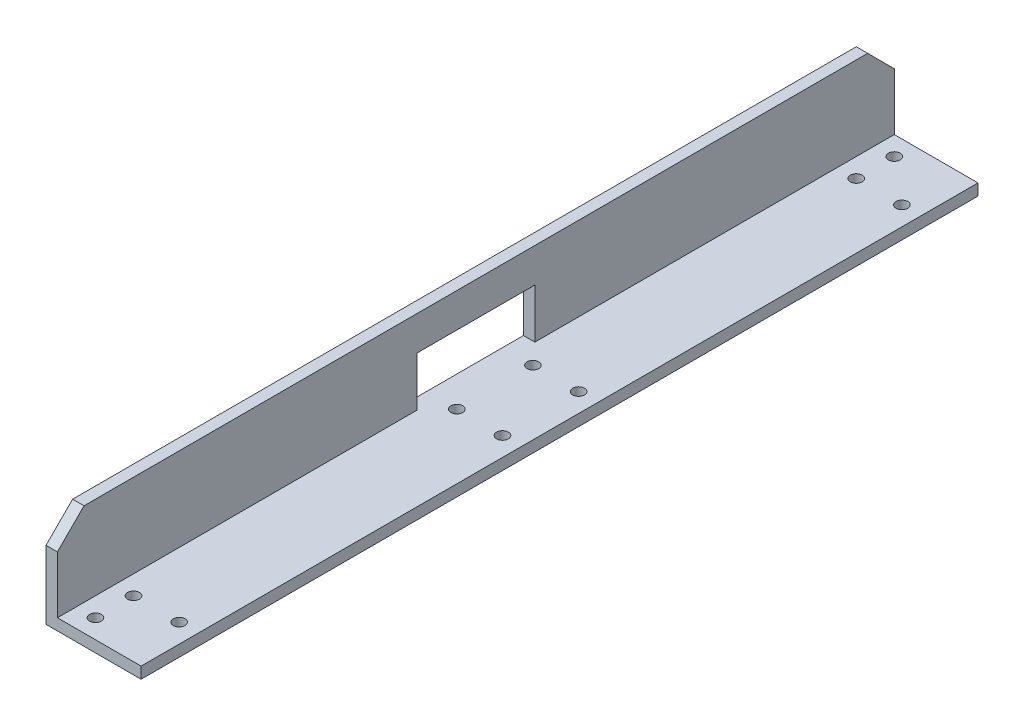
SolidWorks part; units mm, degrees
ref_plane "Front Plane" through (0, 0, 0) normal (0, 0, 1) x (1, 0, 0)
ref_plane "Top Plane" through (0, 0, 0) normal (0, 1, 0) x (1, 0, 0)
ref_plane "Right Plane" through (0, 0, 0) normal (1, 0, 0) x (0, 0, -1)
sketch "Sketch1" plane through (0, 0, 0) normal (0, 0, 1) x (1, 0, 0)
  line L0 (0, 0) -> (0, 25)
  line L1 (0, 25) -> (3, 25)
  line L2 (3, 25) -> (3, 3)
  line L3 (3, 3) -> (25, 3)
  line L4 (25, 3) -> (25, 0)
  line L5 (25, 0) -> (0, 0)
  dimension "D1" = 3
  dimension "D2" = 25
extrude "Boss-Extrude1" add sketch "Sketch1" along normal blind 220
sketch "Sketch2" plane through (3, 0, 0) normal (1, 0, 0) x (0, 0, -1)
  line L0 (-220, 3) -> (0, 3) construction
  line L1 (-125.5, 3) -> (-94.5, 3)
  line L2 (-125.5, 3) -> (-125.5, 16)
  line L3 (-125.5, 16) -> (-94.5, 16)
  line L4 (-94.5, 3) -> (-94.5, 16)
  line L5 (-110, 16) -> (-110, 0) construction
  line L6 (-220, 0) -> (0, 0) construction
  dimension "D1" = 31
  dimension "D2" = 13
extrude "Cut-Extrude1" cut sketch "Sketch2" against normal blind 10
sketch "Sketch3" plane through (0, 0, 0) normal (0, -1, 0) x (1, 0, 0)
  line L0 (8, 220) -> (8, 0) construction
  line L2 (0, 0) -> (25, 0) construction
  line L3 (0, 220) -> (0, 0) construction
  line L4 (-195, 220) -> (25, 220) construction
  line L8 (8, 120) -> (20, 120) construction
  line L9 (25, 220) -> (25, 0) construction
  line L10 (20, 100) -> (20, 120) construction
  line L11 (20, 100) -> (8, 100) construction
  line L12 (0, 220) -> (25, 220) construction
  line L13 (20, 205) -> (8, 205) construction
  line L14 (8, 15) -> (20, 15) construction
  line L15 (20, 15) -> (20, 205) construction
  line L16 (0, 110) -> (25, 110) construction
  circle A0 centre (8, 100) radius 1.55
  circle A1 centre (8, 120) radius 1.55
  circle A2 centre (8, 215) radius 1.55
  circle A3 centre (8, 205) radius 1.55
  circle A4 centre (8, 15) radius 1.55
  circle A5 centre (8, 5) radius 1.55
  circle A6 centre (20, 120) radius 1.55
  circle A7 centre (20, 100) radius 1.55
  circle A8 centre (20, 15) radius 1.55
  circle A9 centre (20, 205) radius 1.55
  dimension "D2" = 3.1
  dimension "D1" = 8
  dimension "D3" = 5
  dimension "D4" = 10
  dimension "D5" = 10
  dimension "D6" = 20
  dimension "D7" = 10
  dimension "D8" = 5
  dimension "D9" = 5
  dimension "D10" = 5
extrude "Cut-Extrude2" cut sketch "Sketch3" against normal blind 220
chamfer "Chamfer1" distance 7 angle 45 2 edges at (1.5, 25, 0) (1.5, 25, 220)
